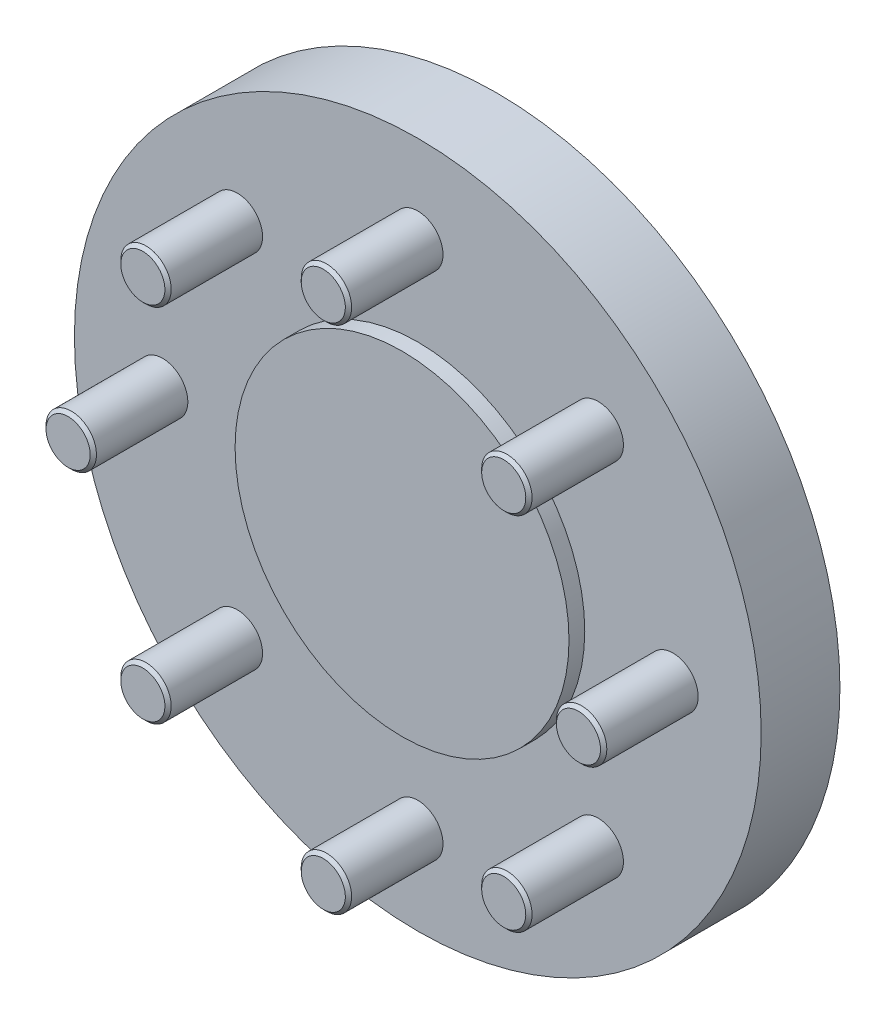
SolidWorks part; units mm, degrees
ref_plane "Front Plane" through (0, 0, 0) normal (0, 0, 1) x (1, 0, 0)
ref_plane "Top Plane" through (0, 0, 0) normal (0, 1, 0) x (1, 0, 0)
ref_plane "Right Plane" through (0, 0, 0) normal (1, 0, 0) x (0, 0, -1)
sketch "Sketch1" plane through (0, 0, 0) normal (0, 1, 0) x (1, 0, 0)
  line L0 (0, 0) -> (0, 75)
  line L1 (0, 75) -> (30, 75)
  line L2 (30, 75) -> (30, 30)
  line L3 (30, 30) -> (109, 30)
  line L4 (109, 30) -> (109, 5)
  line L5 (109, 5) -> (53, 5)
  line L6 (53, 5) -> (53, 0)
  line L7 (53, 0) -> (0, 0)
  dimension "D1" = 75
  dimension "D2" = 53
  dimension "D3" = 56
  dimension "D4" = 25
  dimension "D5" = 30
  dimension "D6" = 45
revolve "Revolve1" add sketch "Sketch1" angle 360 about L0
sketch "Sketch2" plane through (0, 0, -5) normal (0, 0, 1) x (1, 0, 0)
  circle A0 centre (81, 0) radius 8
  point P2 (0, 0)
  dimension "D1" = 16
  dimension "D2" = 81
extrude "Boss-Extrude1" add sketch "Sketch2" along normal blind 30
chamfer "Chamfer1" distance 1 angle 45 1 edges at (89, 0, 25)
pattern_circular "CirPattern1" count 8 over 360 about axis through (0, 0, 0) along (0, 0, 1) of "Boss-Extrude1", "Chamfer1"
